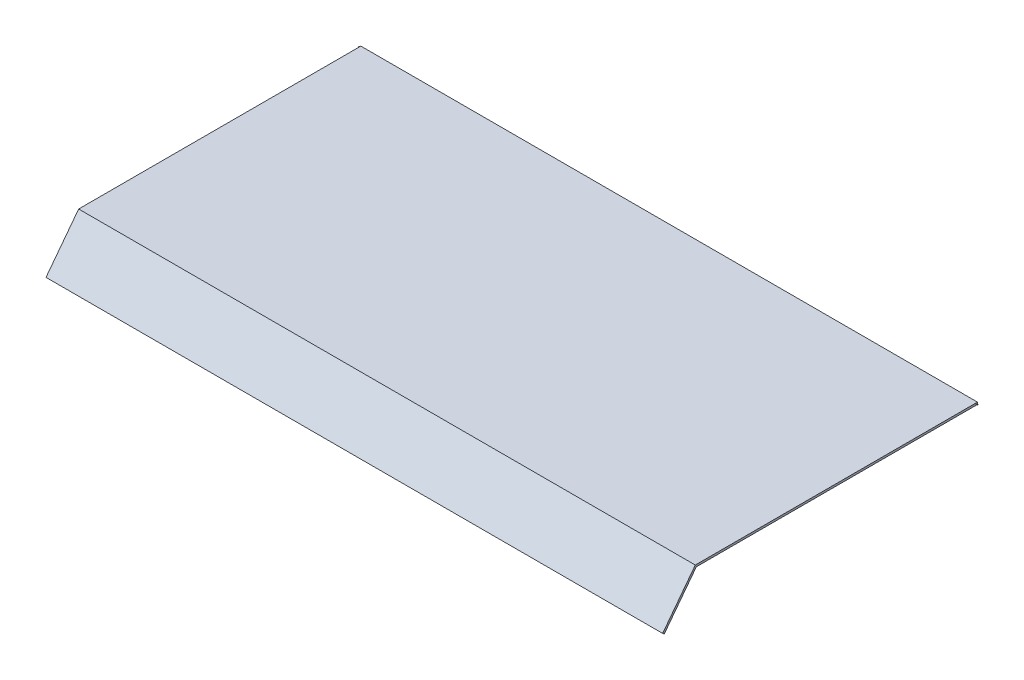
SolidWorks part; units mm, degrees
ref_plane "Alzado" through (0, 0, 0) normal (0, 0, 1) x (1, 0, 0)
ref_plane "Planta" through (0, 0, 0) normal (0, 1, 0) x (1, 0, 0)
ref_plane "Vista lateral" through (0, 0, 0) normal (1, 0, 0) x (0, 0, -1)
sketch "Croquis1" plane through (0, 0, 0) normal (1, 0, 0) x (0, 0, -1)
  line L0 (0, 0) -> (134.5, 0)
  line L1 (0, 0) -> (-15.321, -20.1335)
  line L2 (-0.4956, 1) -> (134.5, 1)
  line L3 (-0.4956, 1) -> (-16.1168, -19.5279)
  line L4 (-15.321, -20.1335) -> (-16.1168, -19.5279)
  line L5 (134.5, 1) -> (134.5, 0)
  dimension "D1" = 127.27
  dimension "D2" = 25.3
  dimension "D3" = 134.5
  dimension "D4" = 1
extrude "Saliente-Extruir1" add sketch "Croquis1" along normal blind 147.5
sketch "Croquis2" plane through (147.5, 0, 0) normal (1, 0, 0) x (0, 0, -1)
  line L0 (134.5, 0.5) -> (133.5, 0.5) construction
  line L1 (134.5, 0) -> (134.5, 1) construction
  circle A0 centre (134, 0.5) radius 0.25
  point P4 (134, 0.5)
  dimension "D1" = 1
extrude "Saliente-Extruir2" add sketch "Croquis2" along normal blind 0.5
mirror "Simetría1" about plane through (0, 0, 0) normal (-1, 0, 0) of bodies 102
